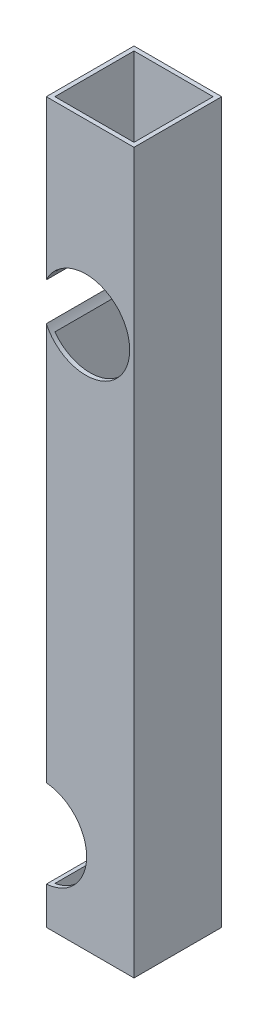
SolidWorks part; units mm, degrees
ref_plane "Front Plane" through (0, 0, 0) normal (0, 0, 1) x (1, 0, 0)
ref_plane "Top Plane" through (0, 0, 0) normal (0, 1, 0) x (1, 0, 0)
ref_plane "Right Plane" through (0, 0, 0) normal (1, 0, 0) x (0, 0, -1)
sketch "Sketch1" plane through (0, 0, 0) normal (0, 1, 0) x (1, 0, 0)
  line L1 (-12.7, -12.7) -> (12.7, -12.7)
  line L2 (-12.7, -12.7) -> (-12.7, 12.7)
  line L3 (-12.7, 12.7) -> (12.7, 12.7)
  line L4 (12.7, -12.7) -> (12.7, 12.7)
  line L5 (-12.7, -12.7) -> (12.7, 12.7) construction
  line L6 (-12.7, 12.7) -> (12.7, -12.7) construction
  line L7 (11.4554, -11.4554) -> (-11.4554, -11.4554)
  line L8 (11.4554, -11.4554) -> (11.4554, 11.4554)
  line L9 (11.4554, 11.4554) -> (-11.4554, 11.4554)
  line L10 (-11.4554, -11.4554) -> (-11.4554, 11.4554)
  line L11 (11.4554, -11.4554) -> (-11.4554, 11.4554) construction
  line L12 (11.4554, 11.4554) -> (-11.4554, -11.4554) construction
  point P0 (0, 0)
  point P6 (0, 0)
  dimension "D1" = 25.4
  dimension "D2" = 1.2446
extrude "Boss-Extrude1" add sketch "Sketch1" along normal blind 208.28
sketch "Sketch2" plane through (0, 0, 12.7) normal (0, 0, 1) x (1, 0, 0)
  line L1 (-12.7, 0) -> (12.7, 0) construction
  line L2 (-12.7, 208.28) -> (12.7, 208.28) construction
  line L5 (12.7, 208.28) -> (12.7, 0) construction
  circle A0 centre (-13.772, 23.551) radius 12.756
  circle A1 centre (-1.2446, 156.845) radius 12.7
  point P4 (-22.0321, 169.7271)
  dimension "D4" = 10.795
  dimension "D3" = 25.512
  dimension "D5" = 25.4
  dimension "D6" = 38.735
  dimension "D1" = 1.2446
  dimension "D2" = 13.716
extrude "Cut-Extrude1" cut sketch "Sketch2" against normal blind 209.55
